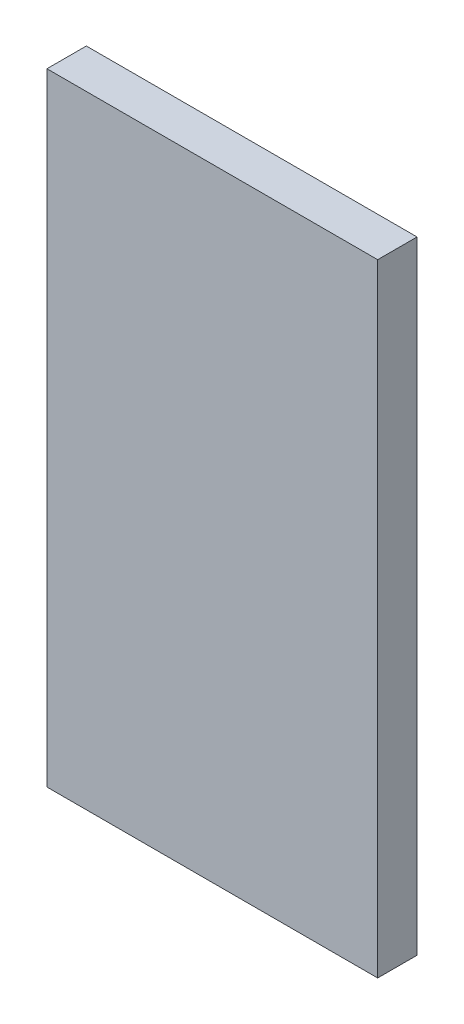
SolidWorks part; units mm, degrees
material "1.0116 (S235J2G3)"
ref_plane "Front Plane" through (0, 0, 0) normal (0, 0, 1) x (1, 0, 0)
ref_plane "Top Plane" through (0, 0, 0) normal (0, 1, 0) x (1, 0, 0)
ref_plane "Right Plane" through (0, 0, 0) normal (1, 0, 0) x (0, 0, -1)
sketch "Sketch1" plane through (0, 0, 0) normal (0, 0, 1) x (1, 0, 0)
  line L1 (-42, -79) -> (42, -79)
  line L2 (-42, -79) -> (-42, 79)
  line L3 (-42, 79) -> (42, 79)
  line L4 (42, -79) -> (42, 79)
  line L5 (-42, -79) -> (42, 79) construction
  line L6 (-42, 79) -> (42, -79) construction
  point P0 (0, 0)
  dimension "D1" = 84
  dimension "D2" = 158
extrude "Boss-Extrude1" add sketch "Sketch1" along normal blind 10
